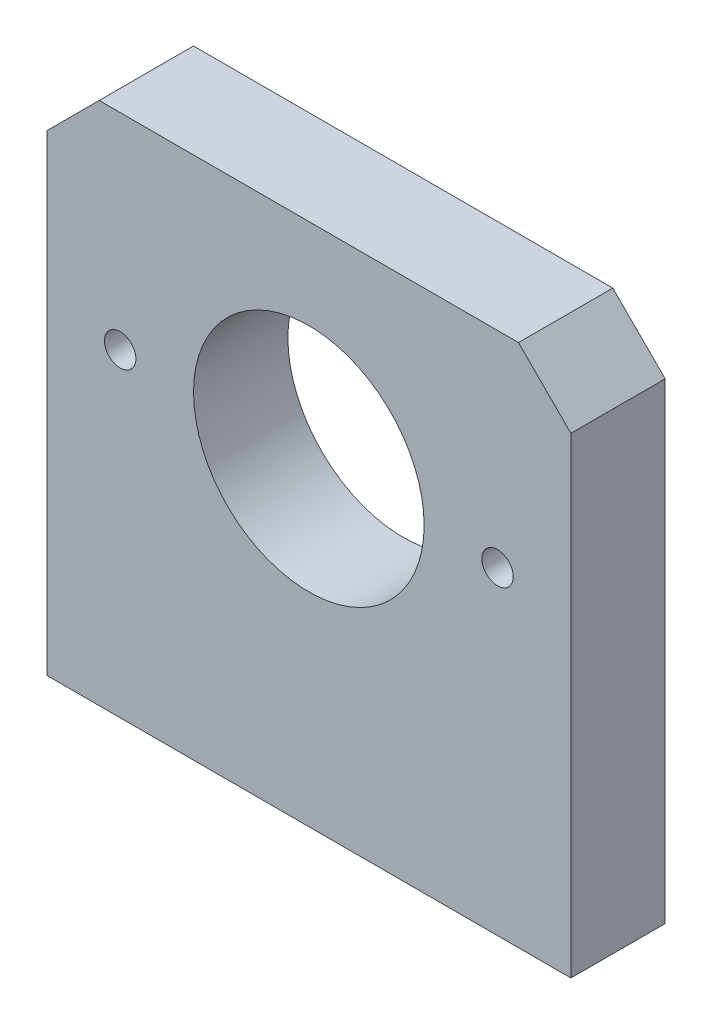
SolidWorks part; units mm, degrees
ref_plane "Front" through (0, 0, 0) normal (0, 0, 1) x (1, 0, 0)
ref_plane "Top" through (0, 0, 0) normal (0, 1, 0) x (1, 0, 0)
ref_plane "Right" through (0, 0, 0) normal (1, 0, 0) x (0, 0, -1)
sketch "Sketch1" plane through (0, 0, 0) normal (0, 0, 1) x (1, 0, 0)
  line L0 (25, 0) -> (25, 50) construction
  line L1 (0, 0) -> (50, 0)
  line L2 (0, 0) -> (0, 45)
  line L3 (5, 50) -> (45, 50)
  line L4 (50, 0) -> (50, 45)
  line L5 (0, 45) -> (5, 50)
  line L6 (50, 45) -> (45, 50)
  line L7 (0, 30.4) -> (50, 30.4) construction
  circle A0 centre (25, 30.4) radius 11
  circle A1 centre (7, 30.4) radius 1.5
  circle A2 centre (43, 30.4) radius 1.5
  point P11 (25, 30.4)
  dimension "D6" = 22
  dimension "D8" = 3
  dimension "D1" = 135
  dimension "D2" = 5
  dimension "D4" = 50
  dimension "D5" = 30.4
  dimension "D7" = 18
  dimension "D3" = 50
extrude "Boss-Extrude1" add sketch "Sketch1" along normal blind 9
equation "\"material-thickness\" = 9mm"
equation "\"spindle-thread-height\" = 30.4mm ' Height from the base to the spindle for the stepper motor / Servo"
equation "\"spindle-thread-rbearing-diameter\" = 22mm ' Outer diameter of the rotational bearing"
equation "\"D5@Sketch1\"=\"spindle-thread-height\""
equation "\"D6@Sketch1\"=\"spindle-thread-rbearing-diameter\""
equation "\"D1@Boss-Extrude1\"=\"material-thickness\""
